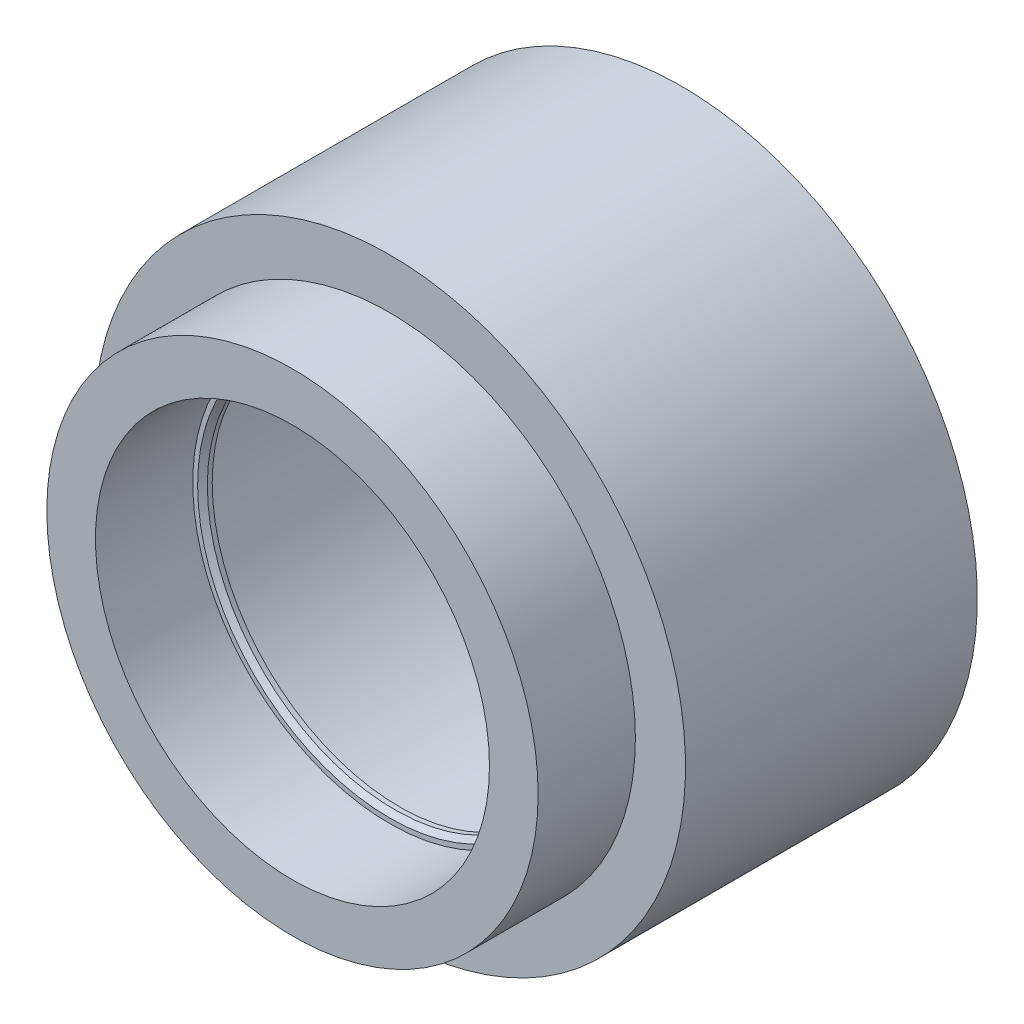
SolidWorks part; units mm, degrees
ref_plane "Front Plane" through (0, 0, 0) normal (0, 0, 1) x (1, 0, 0)
ref_plane "Top Plane" through (0, 0, 0) normal (0, 1, 0) x (1, 0, 0)
ref_plane "Right Plane" through (0, 0, 0) normal (1, 0, 0) x (0, 0, -1)
sketch "Sketch2" plane through (0, 0, 0) normal (0, 0, 1) x (1, 0, 0)
  circle A0 centre (0, 0) radius 20.25
  circle A1 centre (0, 0) radius 25.25
  dimension "D1" = 40.5
  dimension "D2" = 5
extrude "Boss-Extrude1" add sketch "Sketch2" along normal blind 10
sketch "Sketch3" plane through (0, 0, 0) normal (0, 0, -1) x (-1, 0, 0)
  circle A0 centre (0, 0) radius 19.25
  circle A1 centre (0, 0) radius 30.4
  circle A2 centre (0, 0) radius 20.25 construction
  dimension "D1" = 60.8
  dimension "D2" = 1
extrude "Boss-Extrude2" add sketch "Sketch3" along normal blind 30
sketch "Sketch4" plane through (0, 0, -30) normal (0, 0, -1) x (-1, 0, 0)
  circle A0 centre (0, 0) radius 25.5
  dimension "D1" = 51
extrude "Cut-Extrude1" cut sketch "Sketch4" against normal offset from surface (29 mm away) 1 contours A0 up to face at (-19.25, 0, 0)
chamfer "Chamfer2" distance 0.5 angle 45 1 edges at (-19.25, 0, 0)
